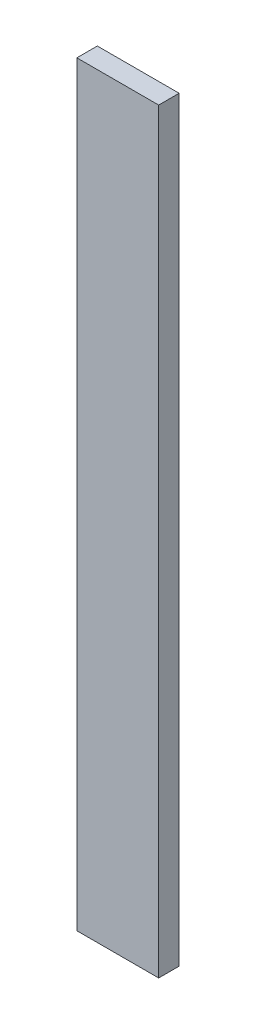
SolidWorks part; units mm, degrees
material "6061 Alloy"
ref_plane "Front Plane" through (0, 0, 0) normal (0, 0, 1) x (1, 0, 0)
ref_plane "Top Plane" through (0, 0, 0) normal (0, 1, 0) x (1, 0, 0)
ref_plane "Right Plane" through (0, 0, 0) normal (1, 0, 0) x (0, 0, -1)
sketch "Sketch1" plane through (0, 0, 0) normal (0, 0, 1) x (1, 0, 0)
  line L1 (-12.7, 117.348) -> (12.7, 117.348)
  line L2 (-12.7, 117.348) -> (-12.7, -117.348)
  line L3 (-12.7, -117.348) -> (12.7, -117.348)
  line L4 (12.7, 117.348) -> (12.7, -117.348)
  line L5 (-12.7, 117.348) -> (12.7, -117.348) construction
  line L6 (-12.7, -117.348) -> (12.7, 117.348) construction
  point P0 (0, 0)
  dimension "D1" = 234.696
extrude "Boss-Extrude1" add sketch "Sketch1" along normal blind 6.35
